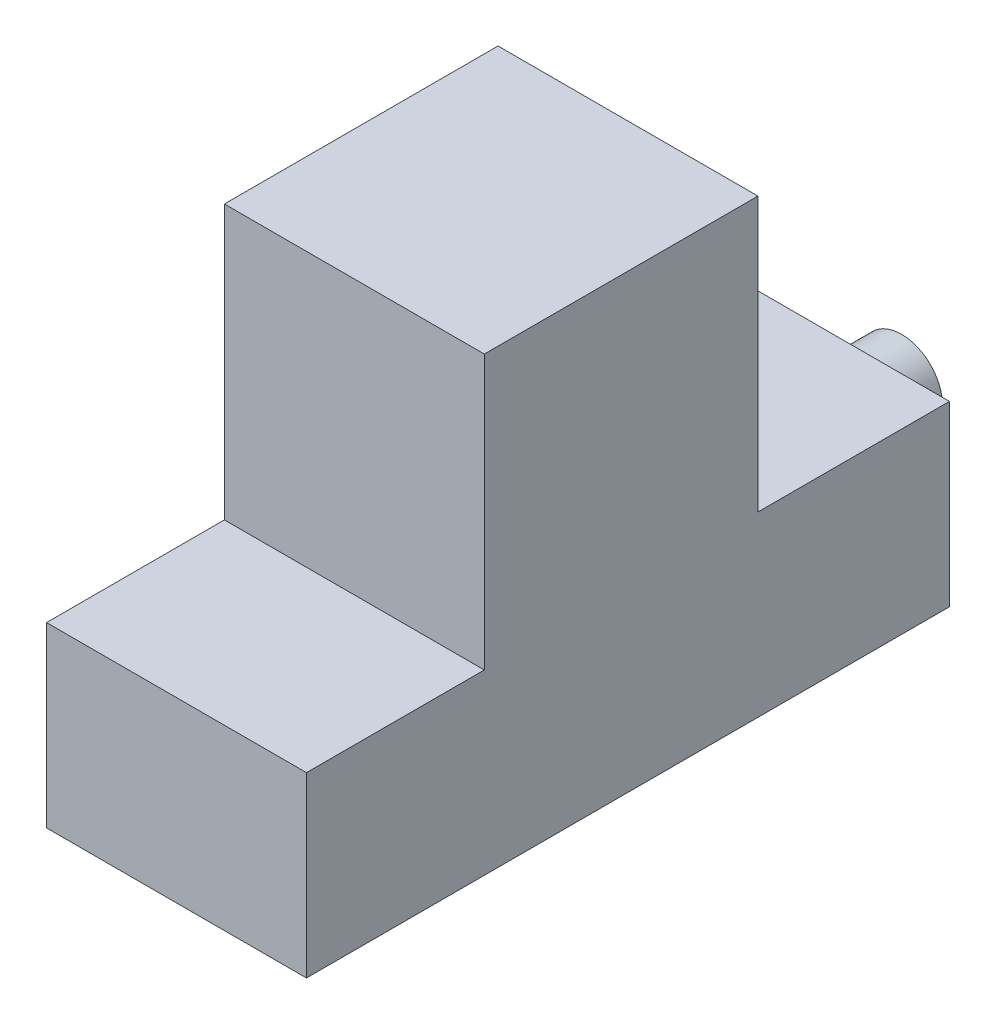
SolidWorks part; units mm, degrees
material "ABS"
ref_plane "Front Plane" through (0, 0, 0) normal (0, 0, 1) x (1, 0, 0)
ref_plane "Top Plane" through (0, 0, 0) normal (0, 1, 0) x (1, 0, 0)
ref_plane "Right Plane" through (0, 0, 0) normal (1, 0, 0) x (0, 0, -1)
sketch "Sketch1" plane through (0, 0, 0) normal (0, 0, 1) x (1, 0, 0)
  line L1 (-4.75, -3.25) -> (4.75, -3.25)
  line L2 (-4.75, -3.25) -> (-4.75, 3.25)
  line L3 (-4.75, 3.25) -> (4.75, 3.25)
  line L4 (4.75, -3.25) -> (4.75, 3.25)
  line L5 (-4.75, -3.25) -> (4.75, 3.25) construction
  line L6 (-4.75, 3.25) -> (4.75, -3.25) construction
  point P0 (0, 0)
  dimension "D1" = 6.5
  dimension "D2" = 9.5
extrude "Boss-Extrude1" add sketch "Sketch1" along normal blind 11 and the other way blind 12
sketch "Sketch2" plane through (0, 3.25, 0) normal (0, 1, 0) x (1, 0, 0)
  line L0 (0, -11) -> (0, -5) construction
  line L1 (4.75, -11) -> (-4.75, -11) construction
  line L2 (-4.75, -5) -> (4.75, -5)
  line L3 (4.75, 12) -> (4.75, -11) construction
  line L4 (-4.75, -5) -> (-4.75, 5)
  line L5 (-4.75, 12) -> (-4.75, -11) construction
  line L6 (-4.75, 5) -> (4.75, 5)
  line L7 (4.75, 5) -> (4.75, -5)
  point P10 (0, -5)
  dimension "D1" = 6
  dimension "D2" = 10
extrude "Boss-Extrude2" add sketch "Sketch2" along normal blind 10
sketch "Sketch3" plane through (0, 0, -12) normal (0, 0, -1) x (-1, 0, 0)
  line L0 (0, 3.25) -> (0, -3.25) construction
  line L1 (-4.75, 3.25) -> (4.75, 3.25) construction
  line L2 (4.75, -3.25) -> (-4.75, -3.25) construction
  circle A0 centre (0, 0) radius 1.5
  dimension "D1" = 3
extrude "Boss-Extrude3" add sketch "Sketch3" along normal blind 3
sketch "Sketch4" plane through (0, 0, 11) normal (0, 0, 1) x (1, 0, 0)
  line L1 (-4.75, 3.25) -> (4.75, 3.25)
  line L2 (-4.75, 3.25) -> (-4.75, -3.25)
  line L3 (-4.75, -3.25) -> (4.75, -3.25)
  line L4 (4.75, 3.25) -> (4.75, -3.25)
extrude "Boss-Extrude4" add sketch "Sketch4" along normal blind 0.5
